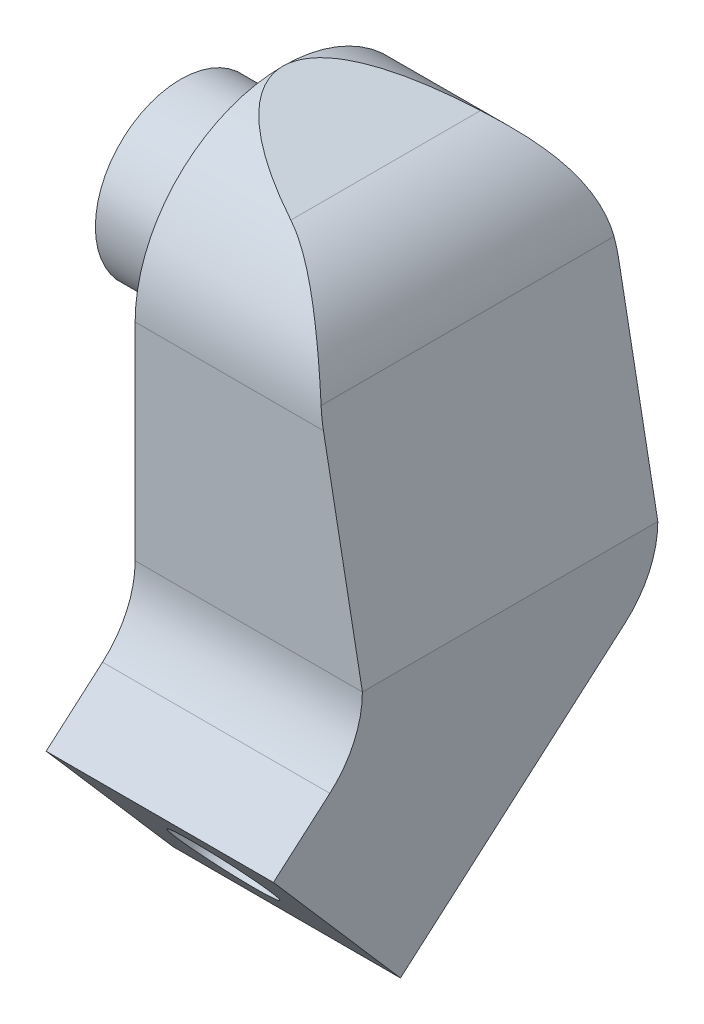
SolidWorks part; units mm, degrees
ref_plane "Alzado" through (0, 0, 0) normal (0, 0, 1) x (1, 0, 0)
ref_plane "Planta" through (0, 0, 0) normal (0, 1, 0) x (1, 0, 0)
ref_plane "Vista lateral" through (0, 0, 0) normal (1, 0, 0) x (0, 0, -1)
sketch "Croquis2" plane through (0, 0, 0) normal (1, 0, 0) x (0, 0, -1)
  line L0 (7.8, 9.2447) -> (7.8, -1.6754)
  line L1 (6.0788, -5.4503) -> (-5.7895, -15.7589)
  line L2 (-5.7895, -15.7589) -> (-12.4978, -8.0357)
  line L3 (-7.8, 9.2447) -> (-7.8, -1.6754)
  line L4 (-9.5212, -5.4503) -> (-12.4978, -8.0357)
  arc A0 (7.8, 9.2447) -> (-7.8, 9.2447) centre (0, 9.2447) ccw
  arc A1 (7.8, -1.6754) -> (6.0788, -5.4503) centre (2.8, -1.6754) cw
  arc A2 (-7.8, -1.6754) -> (-9.5212, -5.4503) centre (-12.8, -1.6754) cw
  point P9 (7.8, -3.9553)
  point P12 (0, 17.0447)
  dimension "D2" = 15.6
  dimension "D4" = 5
  dimension "D5" = 5
  dimension "D1" = 13.2
  dimension "D3" = 18
extrude "Saliente-Extruir1" add sketch "Croquis2" along normal mid plane 12
sketch "Croquis3" plane through (0, 0, 0) normal (0, 0, 1) x (1, 0, 0)
  line L0 (-6, 17.0447) -> (-0.5699, 15.2244)
  line L1 (3.7519, 10.2642) -> (6, -1.6754)
  line L2 (6, -1.6754) -> (6, 17.0447)
  line L3 (6, 17.0447) -> (-6, 17.0447)
  arc A0 (-0.5699, 15.2244) -> (3.7519, 10.2642) centre (-2.6359, 9.0615) cw
  dimension "D1" = 6.5
  dimension "D2" = 5.7271
  dimension "D3" = 12.1495
extrude "Cortar-Extruir1" cut sketch "Croquis3" against normal through all both and the other way through all contours L3 L0 A0 L1 L2
sketch "Croquis4" plane through (0, -9.6429, 11.1018) normal (0, -0.6558, 0.755) x (1, 0, 0)
  line L0 (-6, 2.1288) -> (-6, -8.101) construction
  line L1 (6, 2.1288) -> (-6, 2.1288) construction
  circle A0 centre (0, -2.9912) radius 2.5
  dimension "D1" = 5
  dimension "D2" = 6
  dimension "D3" = 5.12
extrude "Cortar-Extruir2" cut sketch "Croquis4" against normal blind 5.4 and the other way through all
sketch "Croquis5" plane through (-6, 0, 0) normal (-1, 0, 0) x (0, 0, 1)
  line L0 (7.8, 9.2447) -> (7.8, -1.6754) construction
  circle A0 centre (0, 9.2447) radius 4.5
  dimension "D1" = 9
  dimension "D2" = 7.8
  dimension "D3" = 7.8
extrude "Saliente-Extruir2" add sketch "Croquis5" along normal blind 5.4
